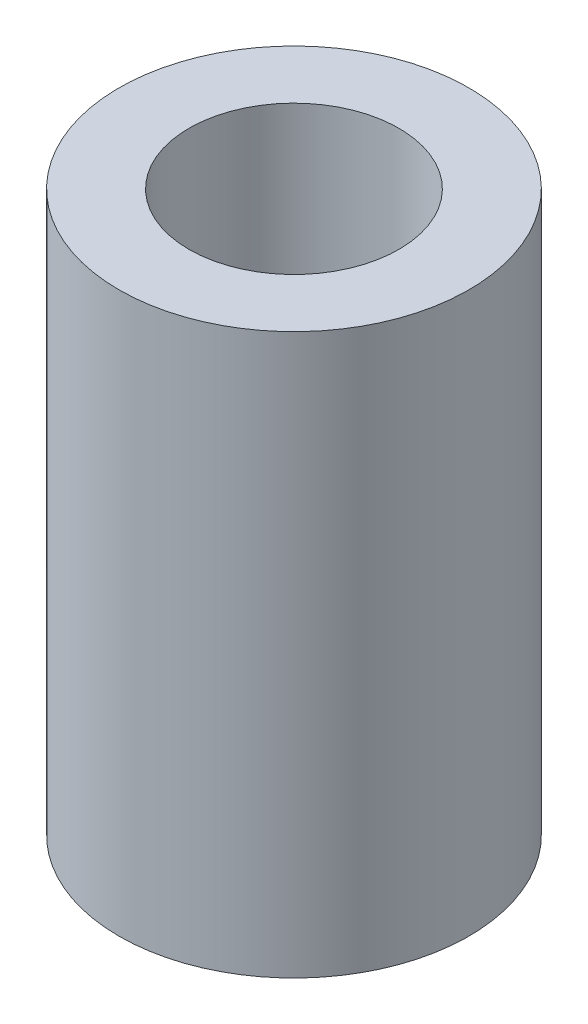
SolidWorks part; units mm, degrees
ref_plane "Спереди" through (0, 0, 0) normal (0, 0, 1) x (1, 0, 0)
ref_plane "Сверху" through (0, 0, 0) normal (0, 1, 0) x (1, 0, 0)
ref_plane "Справа" through (0, 0, 0) normal (1, 0, 0) x (0, 0, -1)
sketch "Эскиз1" plane through (0, 0, 0) normal (0, 1, 0) x (1, 0, 0)
  circle A0 centre (0, 0) radius 1.5
  circle A1 centre (0, 0) radius 2.5
extrude "Бобышка-Вытянуть1" add sketch "Эскиз1" along normal blind 8
